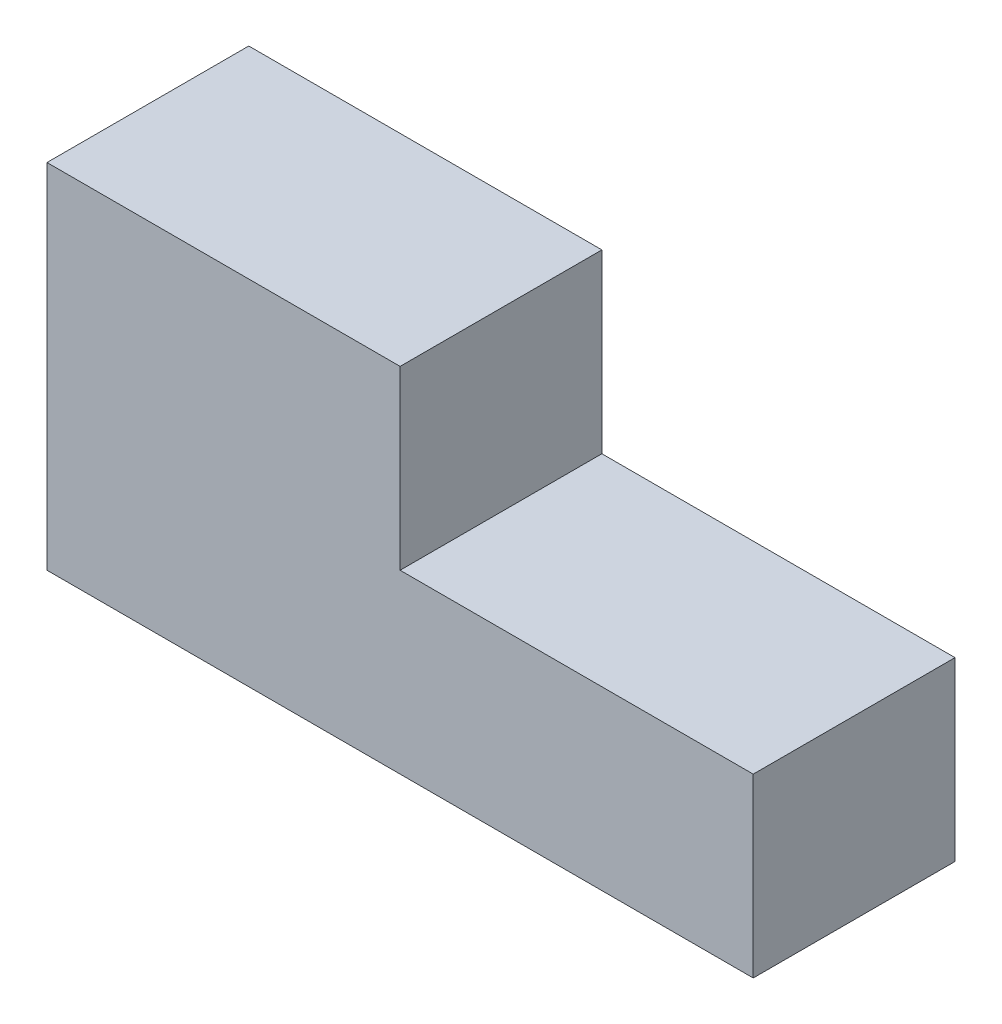
SolidWorks part; units mm, degrees
ref_plane "Front Plane" through (0, 0, 0) normal (0, 0, 1) x (1, 0, 0)
ref_plane "Top Plane" through (0, 0, 0) normal (0, 1, 0) x (1, 0, 0)
ref_plane "Right Plane" through (0, 0, 0) normal (1, 0, 0) x (0, 0, -1)
sketch "Sketch2" plane through (0, 0, 0) normal (0, 0, 1) x (1, 0, 0)
  line L0 (-45.9931, 20.0143) -> (-45.9931, -24.4357)
  line L1 (-45.9931, -24.4357) -> (42.9069, -24.4357)
  line L2 (42.9069, -24.4357) -> (42.9069, -2.2107)
  line L3 (42.9069, -2.2107) -> (-1.5431, -2.2107)
  line L4 (-1.5431, -2.2107) -> (-1.5431, 20.0143)
  line L5 (-1.5431, 20.0143) -> (-45.9931, 20.0143)
  dimension "D1" = 44.45
  dimension "D2" = 88.9
  dimension "D3" = 44.45
  dimension "D4" = 22.225
extrude "Boss-Extrude1" add sketch "Sketch2" along normal mid plane 25.4
